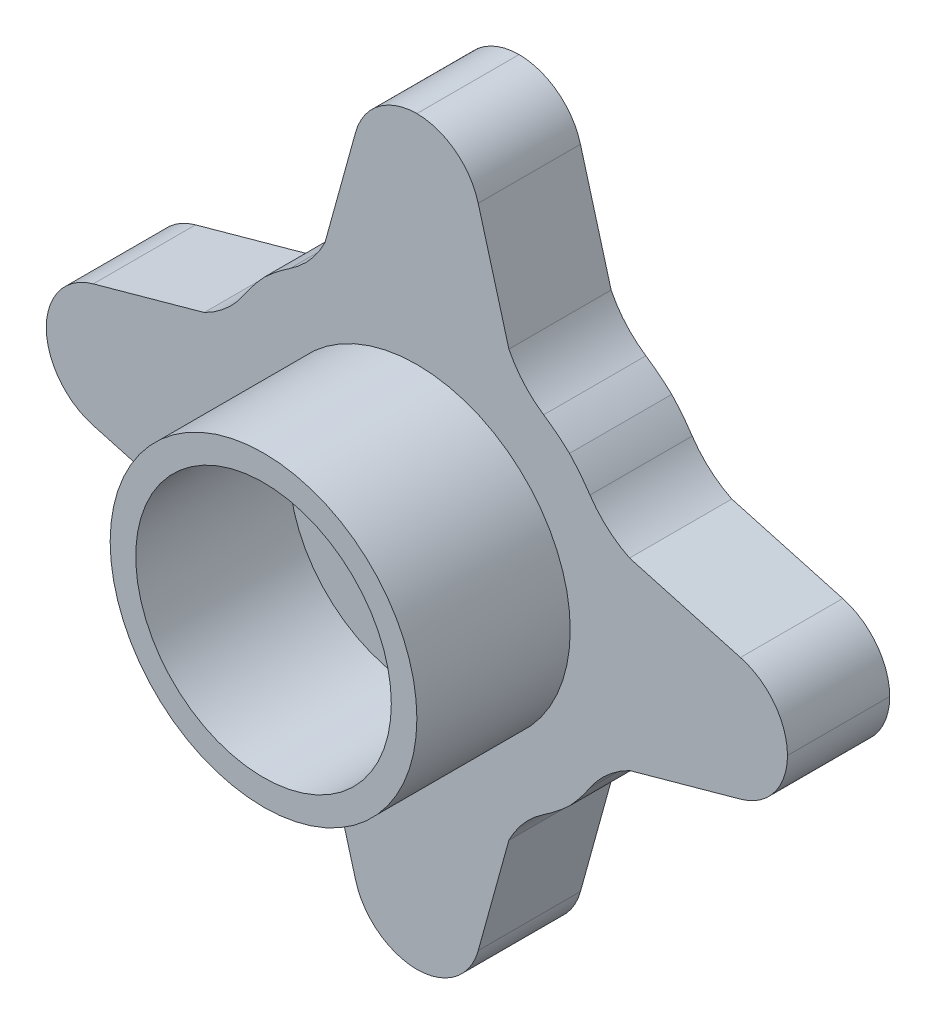
SolidWorks part; units mm, degrees
ref_plane "Front Plane" through (0, 0, 0) normal (0, 0, 1) x (1, 0, 0)
ref_plane "Top Plane" through (0, 0, 0) normal (0, 1, 0) x (1, 0, 0)
ref_plane "Right Plane" through (0, 0, 0) normal (1, 0, 0) x (0, 0, -1)
sketch "Sketch1" plane through (0, 0, 0) normal (0, 0, 1) x (1, 0, 0)
  line L0 (0, 7.25) -> (0, -7.25) construction
  line L1 (0, -7.25) -> (0, 0) construction
  line L2 (6.1605, 0) -> (-6.1605, 0) construction
  line L3 (-1.2, 6.33) -> (-1.8, 4.16)
  line L4 (1.2, -6.33) -> (1.8, -4.16)
  line L5 (6.33, -1.2) -> (4.16, -1.8)
  line L6 (6.33, 1.2) -> (4.16, 1.8)
  line L7 (1.2, 6.33) -> (1.8, 4.16)
  line L8 (-6.33, 1.2) -> (-4.16, 1.8)
  line L9 (-6.33, -1.2) -> (-4.16, -1.8)
  line L10 (-1.2, -6.33) -> (-1.8, -4.16)
  arc A0 (0, -7.25) -> (1.2, -6.33) centre (-0.0057, -6) ccw
  arc A1 (1.8, -4.16) -> (2.48, -3.3864) centre (3.5915, -5.049) cw
  arc A2 (2.48, -3.3864) -> (2.9857, -2.9857) centre (0.2569, -0.061) ccw
  arc A3 (3.3864, -2.48) -> (2.9857, -2.9857) centre (0.061, -0.2569) cw
  arc A4 (4.16, -1.8) -> (3.3864, -2.48) centre (5.049, -3.5915) ccw
  arc A5 (7.25, 0) -> (6.33, -1.2) centre (6, 0.0057) cw
  arc A6 (7.25, 0) -> (6.33, 1.2) centre (6, -0.0057) ccw
  arc A7 (4.16, 1.8) -> (3.3864, 2.48) centre (5.049, 3.5915) cw
  arc A8 (3.3864, 2.48) -> (2.9857, 2.9857) centre (0.061, 0.2569) ccw
  arc A9 (2.48, 3.3864) -> (2.9857, 2.9857) centre (0.2569, 0.061) cw
  arc A10 (1.8, 4.16) -> (2.48, 3.3864) centre (3.5915, 5.049) ccw
  arc A11 (0, 7.25) -> (1.2, 6.33) centre (-0.0057, 6) cw
  arc A12 (0, 7.25) -> (-1.2, 6.33) centre (0.0057, 6) ccw
  arc A13 (-1.8, 4.16) -> (-2.48, 3.3864) centre (-3.5915, 5.049) cw
  arc A14 (-2.48, 3.3864) -> (-2.9857, 2.9857) centre (-0.2569, 0.061) ccw
  arc A15 (-3.3864, 2.48) -> (-2.9857, 2.9857) centre (-0.061, 0.2569) cw
  arc A16 (-4.16, 1.8) -> (-3.3864, 2.48) centre (-5.049, 3.5915) ccw
  arc A17 (-7.25, 0) -> (-6.33, 1.2) centre (-6, -0.0057) cw
  arc A18 (-7.25, 0) -> (-6.33, -1.2) centre (-6, 0.0057) ccw
  arc A19 (-4.16, -1.8) -> (-3.3864, -2.48) centre (-5.049, -3.5915) cw
  arc A20 (-3.3864, -2.48) -> (-2.9857, -2.9857) centre (-0.061, -0.2569) ccw
  arc A21 (-2.48, -3.3864) -> (-2.9857, -2.9857) centre (-0.2569, -0.061) cw
  arc A22 (-1.8, -4.16) -> (-2.48, -3.3864) centre (-3.5915, -5.049) ccw
  arc A23 (0, -7.25) -> (-1.2, -6.33) centre (0.0057, -6) cw
  point P4 (0, 0)
  point P11 (0, 0)
  dimension "D5" = 1.25
  dimension "D10" = 2
  dimension "D13" = 4
  dimension "D1" = 7.25
  dimension "D3" = 0.92
  dimension "D4" = 1.2
  dimension "D6" = 2.17
  dimension "D7" = 0.6
  dimension "D8" = 0.68
  dimension "D9" = 1.03
extrude "Boss-Extrude1" add sketch "Sketch1" along normal blind 2
sketch "Sketch2" plane through (0, 0, 2) normal (0, 0, 1) x (1, 0, 0)
  circle A0 centre (0, 0) radius 3
  circle A1 centre (0, 0) radius 2.5
  dimension "D1" = 6
  dimension "D2" = 5
extrude "Boss-Extrude2" add sketch "Sketch2" along normal blind 3
sketch "Sketch3" plane through (0, 0, 0) normal (0, 0, -1) x (-1, 0, 0)
  circle A0 centre (0, 0) radius 1
  dimension "D1" = 2
extrude "Cut-Extrude1" cut sketch "Sketch3" against normal blind 1
sketch "Sketch4" plane through (0, 0, 0) normal (0, 0, 1) x (1, 0, 0)
  circle A0 centre (0, 0) radius 0.5
  dimension "D1" = 1
extrude "Cut-Extrude2" cut sketch "Sketch4" along normal through all
